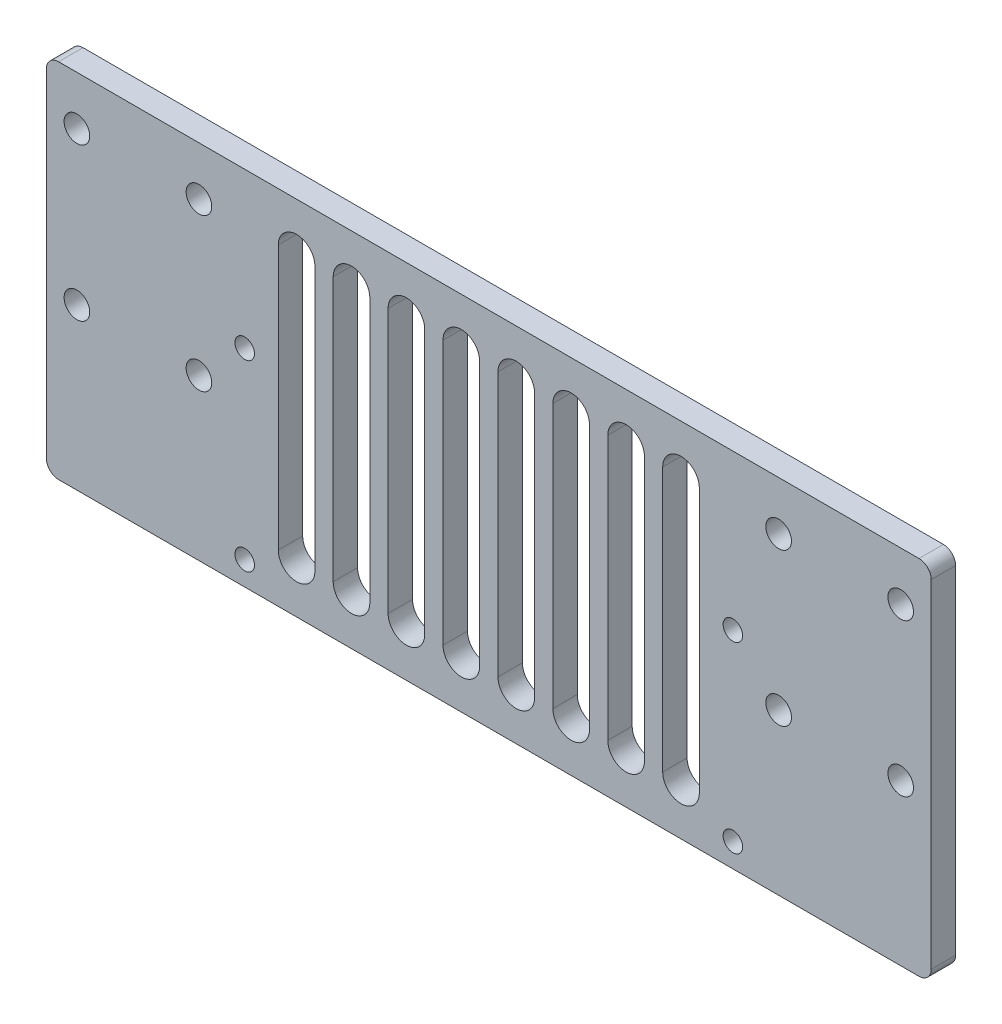
SolidWorks part; units mm, degrees
material "Thornel Mat VMA"
ref_plane "前视基准面" through (0, 0, 0) normal (0, 0, 1) x (1, 0, 0)
ref_plane "上视基准面" through (0, 0, 0) normal (0, 1, 0) x (1, 0, 0)
ref_plane "右视基准面" through (0, 0, 0) normal (1, 0, 0) x (0, 0, -1)
other "Configuration Table"
sketch "草图1" plane through (0, 0, 0) normal (0, 0, 1) x (1, 0, 0)
  line L1 (-72.5, 29.65) -> (72.5, 29.65)
  line L2 (-72.5, 29.65) -> (-72.5, -29.65)
  line L3 (-72.5, -29.65) -> (72.5, -29.65)
  line L4 (72.5, 29.65) -> (72.5, -29.65)
  line L5 (-72.5, 29.65) -> (72.5, -29.65) construction
  line L6 (-72.5, -29.65) -> (72.5, 29.65) construction
  point P0 (0, 0)
  dimension "D1" = 59.3
  dimension "D2" = 145
extrude "凸台-拉伸1" add sketch "草图1" along normal blind 4
sketch "草图2" plane through (0, 0, 4) normal (0, 0, 1) x (1, 0, 0)
  line L0 (72.5, 29.65) -> (-72.5, 29.65) construction
  line L1 (-67.5, 21.65) -> (67.5, 21.65) construction
  line L2 (-67.5, 21.65) -> (-67.5, -3.35) construction
  line L3 (-67.5, -3.35) -> (67.5, -3.35) construction
  line L4 (67.5, 21.65) -> (67.5, -3.35) construction
  line L5 (-67.5, 21.65) -> (67.5, -3.35) construction
  line L6 (-67.5, -3.35) -> (67.5, 21.65) construction
  line L8 (-47.5, 21.65) -> (47.5, 21.65) construction
  line L9 (-47.5, 21.65) -> (-47.5, -3.35) construction
  line L10 (-47.5, -3.35) -> (47.5, -3.35) construction
  line L11 (47.5, 21.65) -> (47.5, -3.35) construction
  line L12 (-47.5, 21.65) -> (47.5, -3.35) construction
  line L13 (-47.5, -3.35) -> (47.5, 21.65) construction
  circle A0 centre (-67.5, 21.65) radius 2.1
  circle A1 centre (67.5, 21.65) radius 2.1
  circle A2 centre (67.5, -3.35) radius 2.1
  circle A3 centre (-67.5, -3.35) radius 2.1
  circle A4 centre (-47.5, 21.65) radius 2.1
  circle A5 centre (47.5, 21.65) radius 2.1
  circle A6 centre (47.5, -3.35) radius 2.1
  circle A7 centre (-47.5, -3.35) radius 2.1
  point P0 (0, 9.15)
  point P5 (0, 9.15)
  dimension "D6" = 4.2
  dimension "D10" = 4.2
  dimension "D1" = 25
  dimension "D2" = 135
  dimension "D3" = 8
  dimension "D7" = 95
  dimension "D4" = 2
  dimension "D5" = 2
  dimension "D8" = 2
  dimension "D9" = 2
extrude "切除-拉伸1" cut sketch "草图2" against normal blind 4
sketch "草图3" plane through (0, 0, 4) normal (0, 0, 1) x (1, 0, 0)
  line L0 (72.5, 29.65) -> (-72.5, 29.65) construction
  line L1 (-40, 4.25) -> (40, 4.25) construction
  line L2 (-40, 4.25) -> (-40, -25.75) construction
  line L3 (-40, -25.75) -> (40, -25.75) construction
  line L4 (40, 4.25) -> (40, -25.75) construction
  line L5 (-40, 4.25) -> (40, -25.75) construction
  line L6 (-40, -25.75) -> (40, 4.25) construction
  circle A0 centre (-40, 4.25) radius 1.6
  circle A1 centre (40, 4.25) radius 1.6
  circle A2 centre (40, -25.75) radius 1.6
  circle A3 centre (-40, -25.75) radius 1.6
  point P0 (0, -10.75)
  dimension "D6" = 3.2
  dimension "D1" = 25.4
  dimension "D2" = 80
  dimension "D3" = 30
  dimension "D4" = 2
  dimension "D5" = 2
extrude "切除-拉伸2" cut sketch "草图3" against normal blind 4
fillet "圆角1" radius 2 4 edges at (-72.5, -29.65, 2) (-72.5, 29.65, 2) (72.5, 29.65, 2) (72.5, -29.65, 2)
sketch "草图4" plane through (0, 0, 4) normal (0, 0, 1) x (1, 0, 0)
  line L0 (-31.5, 21.65) -> (-31.5, -21.65) construction
  line L1 (-28.5, 21.65) -> (-28.5, -21.65)
  line L2 (-34.5, 21.65) -> (-34.5, -21.65)
  line L3 (70.5, 29.65) -> (-70.5, 29.65) construction
  line L4 (-70.5, -29.65) -> (70.5, -29.65) construction
  line L5 (-72.5, 27.65) -> (-72.5, -27.65) construction
  line L6 (-22.5, 21.65) -> (-22.5, -21.65) construction
  line L7 (-19.5, 21.65) -> (-19.5, -21.65)
  line L8 (-25.5, 21.65) -> (-25.5, -21.65)
  line L9 (-13.5, 21.65) -> (-13.5, -21.65) construction
  line L10 (-10.5, 21.65) -> (-10.5, -21.65)
  line L11 (-16.5, 21.65) -> (-16.5, -21.65)
  line L12 (-4.5, 21.65) -> (-4.5, -21.65) construction
  line L13 (-1.5, 21.65) -> (-1.5, -21.65)
  line L14 (-7.5, 21.65) -> (-7.5, -21.65)
  line L15 (4.5, 21.65) -> (4.5, -21.65) construction
  line L16 (7.5, 21.65) -> (7.5, -21.65)
  line L17 (1.5, 21.65) -> (1.5, -21.65)
  line L18 (13.5, 21.65) -> (13.5, -21.65) construction
  line L19 (16.5, 21.65) -> (16.5, -21.65)
  line L20 (10.5, 21.65) -> (10.5, -21.65)
  line L21 (22.5, 21.65) -> (22.5, -21.65) construction
  line L22 (25.5, 21.65) -> (25.5, -21.65)
  line L23 (19.5, 21.65) -> (19.5, -21.65)
  line L24 (31.5, 21.65) -> (31.5, -21.65) construction
  line L25 (34.5, 21.65) -> (34.5, -21.65)
  line L26 (28.5, 21.65) -> (28.5, -21.65)
  arc A0 (-28.5, 21.65) -> (-34.5, 21.65) centre (-31.5, 21.65) ccw
  arc A1 (-34.5, -21.65) -> (-28.5, -21.65) centre (-31.5, -21.65) ccw
  arc A2 (-19.5, 21.65) -> (-25.5, 21.65) centre (-22.5, 21.65) ccw
  arc A3 (-25.5, -21.65) -> (-19.5, -21.65) centre (-22.5, -21.65) ccw
  arc A4 (-10.5, 21.65) -> (-16.5, 21.65) centre (-13.5, 21.65) ccw
  arc A5 (-16.5, -21.65) -> (-10.5, -21.65) centre (-13.5, -21.65) ccw
  arc A6 (-1.5, 21.65) -> (-7.5, 21.65) centre (-4.5, 21.65) ccw
  arc A7 (-7.5, -21.65) -> (-1.5, -21.65) centre (-4.5, -21.65) ccw
  arc A8 (7.5, 21.65) -> (1.5, 21.65) centre (4.5, 21.65) ccw
  arc A9 (1.5, -21.65) -> (7.5, -21.65) centre (4.5, -21.65) ccw
  arc A10 (16.5, 21.65) -> (10.5, 21.65) centre (13.5, 21.65) ccw
  arc A11 (10.5, -21.65) -> (16.5, -21.65) centre (13.5, -21.65) ccw
  arc A12 (25.5, 21.65) -> (19.5, 21.65) centre (22.5, 21.65) ccw
  arc A13 (19.5, -21.65) -> (25.5, -21.65) centre (22.5, -21.65) ccw
  arc A14 (34.5, 21.65) -> (28.5, 21.65) centre (31.5, 21.65) ccw
  arc A15 (28.5, -21.65) -> (34.5, -21.65) centre (31.5, -21.65) ccw
  point P2 (-31.5, 0)
  point P16 (-22.5, 0)
  point P23 (-13.5, 0)
  point P30 (-4.5, 0)
  point P37 (4.5, 0)
  point P44 (13.5, 0)
  point P51 (22.5, 0)
  point P58 (31.5, 0)
  dimension "D1" = 3
  dimension "D2" = 8
  dimension "D3" = 8
  dimension "D4" = 38
  dimension "D6" = 3
  dimension "D5" = 2
  dimension "D7" = 7
extrude "切除-拉伸3" cut sketch "草图4" against normal blind 5
